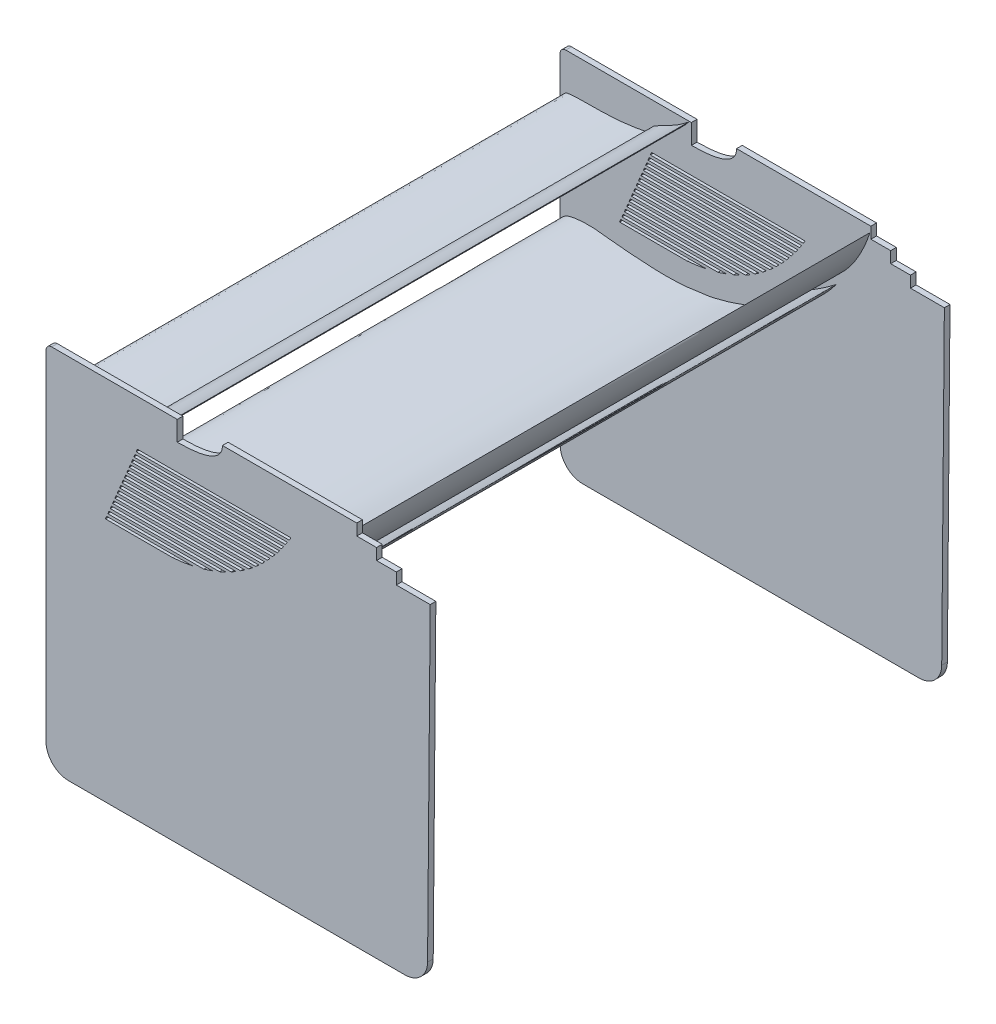
SolidWorks part; units mm, degrees
ref_plane "Front Plane" through (0, 0, 0) normal (0, 0, 1) x (1, 0, 0)
ref_plane "Top Plane" through (0, 0, 0) normal (0, 1, 0) x (1, 0, 0)
ref_plane "Right Plane" through (0, 0, 0) normal (1, 0, 0) x (0, 0, -1)
sketch "Sketch1" plane through (0, 0, 0) normal (0, 0, 1) x (1, 0, 0)
  line L0 (46.9575, 64.3181) -> (1074.8558, 208.7798) construction
sketch "Sketch2" plane through (0, 0, 0) normal (0, 0, 1) x (1, 0, 0)
  line L0 (0, 0) -> (400, 0) construction
  line L1 (0, 0) -> (399.6225, 66.8739) construction
  line L2 (0, 66.8739) -> (0, -66.8739) construction
  line L3 (10.0115, 66.8739) -> (10.0115, -116.1581) construction
  line L4 (20.0229, 66.8739) -> (20.0229, -116.1581) construction
  line L5 (30.0344, 66.8739) -> (30.0344, -116.1581) construction
  line L6 (40.0459, 66.8739) -> (40.0459, -116.1581) construction
  line L7 (50.0573, 66.8739) -> (50.0573, -116.1581) construction
  line L8 (60.0688, 66.8739) -> (60.0688, -116.1581) construction
  line L9 (70.0803, 66.8739) -> (70.0803, -116.1581) construction
  line L10 (80.0918, 66.8739) -> (80.0918, -116.1581) construction
  line L11 (90.1032, 66.8739) -> (90.1032, -116.1581) construction
  line L12 (100.1147, 66.8739) -> (100.1147, -116.1581) construction
  line L13 (110.1262, 66.8739) -> (110.1262, -116.1581) construction
  line L14 (120.1376, 66.8739) -> (120.1376, -116.1581) construction
  line L15 (130.1491, 66.8739) -> (130.1491, -116.1581) construction
  line L16 (140.1606, 66.8739) -> (140.1606, -116.1581) construction
  line L17 (150.172, 66.8739) -> (150.172, -116.1581) construction
  line L18 (160.1835, 66.8739) -> (160.1835, -116.1581) construction
  line L19 (170.195, 66.8739) -> (170.195, -116.1581) construction
  line L20 (180.2064, 66.8739) -> (180.2064, -116.1581) construction
  line L21 (190.2179, 66.8739) -> (190.2179, -116.1581) construction
  line L22 (200.2294, 66.8739) -> (200.2294, -116.1581) construction
  line L23 (210.2408, 66.8739) -> (210.2408, -116.1581) construction
  line L24 (220.2523, 66.8739) -> (220.2523, -116.1581) construction
  line L25 (230.2638, 66.8739) -> (230.2638, -116.1581) construction
  line L26 (240.2753, 66.8739) -> (240.2753, -116.1581) construction
  line L27 (250.2867, 66.8739) -> (250.2867, -116.1581) construction
  line L28 (260.2982, 66.8739) -> (260.2982, -116.1581) construction
  line L29 (270.3097, 66.8739) -> (270.3097, -116.1581) construction
  line L30 (280.3211, 66.8739) -> (280.3211, -116.1581) construction
  line L31 (290.3326, 66.8739) -> (290.3326, -116.1581) construction
  line L32 (300.3441, 66.8739) -> (300.3441, -116.1581) construction
  line L33 (310.3555, 66.8739) -> (310.3555, -116.1581) construction
  line L34 (320.367, 66.8739) -> (320.367, -116.1581) construction
  line L35 (330.3785, 66.8739) -> (330.3785, -116.1581) construction
  line L36 (340.3899, 66.8739) -> (340.3899, -116.1581) construction
  line L37 (350.4014, 66.8739) -> (350.4014, -116.1581) construction
  line L38 (360.4129, 66.8739) -> (360.4129, -116.1581) construction
  line L39 (370.4243, 66.8739) -> (370.4243, -116.1581) construction
  line L40 (380.4358, 66.8739) -> (380.4358, -116.1581) construction
  line L41 (390.4473, 66.8739) -> (390.4473, -116.1581) construction
  line L42 (400.4588, 66.8739) -> (400.4588, -116.1581) construction
  line L43 (836.1007, 66.8739) -> (-36.8556, 66.8739) construction
  line L44 (389.6225, 76.8739) -> (409.6225, 76.8739) construction
  line L45 (399.6225, 90.7703) -> (399.6225, 62.9774) construction
  line L46 (548.1427, 255.362) -> (478.7399, 156.2446) construction
  line L47 (488.7399, 146.2766) -> (482.6971, 142.1346) construction
  line L48 (389.6225, 76.8739) -> (488.7399, 146.2766) construction
  line L51 (488.7399, 194.8045) -> (488.7399, 123.7678) construction
  line L52 (478.7399, 201.6203) -> (478.7399, 116.9521) construction
  line L53 (478.7399, 156.2446) -> (614.5057, 156.2446) construction
  line L54 (389.6225, 83.3039) -> (389.6225, -27.4023) construction
  line L55 (478.7399, 146.2446) -> (614.5057, 146.2446) construction
  spline S0 degree 3 poles (8.4176, 12.2629) (-5.1, -0.6947) (8.0175, -15.4806) (19.5512, -21.724) (30.0167, -25.3022) (39.86, -28.8642) (50.0404, -30.6629) (60.0706, -32.2577) (70.0139, -34.2177) (80.101, -34.56) (90.0931, -35.3652) (100.112, -35.9529) (110.1282, -35.5072) (120.1532, -35.21) (130.1503, -34.2298) (140.19, -33.4102) (150.1782, -31.9134) (160.1704, -30.3713) (170.2408, -29.1636) (180.2083, -27.151) (190.2638, -25.3061) (200.2392, -22.8725) (210.2446, -20.4291) (220.2329, -17.8951) (230.3811, -15.7054) (240.3519, -12.3911) (253.5512, -7.3696) (266.9476, -2.8065) (280.4369, 1.6366) (290.3614, 5.8195) (300.4407, 10.0322) (310.3048, 14.8841) (323.8214, 20.8842) (337.3023, 27.2498) (350.2747, 34.8502) (364.0374, 41.2007) (378.0734, 50.4319) (389.2687, 56.9917) (404.9331, 70.6704) (388.8931, 60.8973) (380.9617, 56.8333) (370.3166, 52.1732) (360.4136, 47.7491) (350.4697, 43.0754) (340.4967, 38.8332) (330.4052, 35.261) (320.3498, 31.8494) (310.3583, 28.3259) (300.4869, 24.6622) (290.3218, 22.3006) (280.2904, 19.7619) (270.4267, 16.765) (260.336, 15.0613) (250.2769, 13.9588) (240.2662, 12.5783) (230.2787, 11.0679) (220.2867, 9.6964) (210.2433, 9.2404) (200.2287, 9.0345) (190.217, 8.2792) (180.2125, 9.1624) (170.1842, 8.7285) (160.1865, 9.5822) (150.1678, 9.9892) (140.1635, 10.7007) (130.146, 11.2145) (120.1214, 11.8409) (110.1328, 12.9697) (100.1148, 13.8501) (90.0938, 14.7159) (80.0796, 15.8427) (56.9177, 18.8475) (32.3828, 18.9634) (8.4176, 12.2629) (-5.1, -0.6947) (8.0175, -15.4806) knots -0.089629 -0.030705 -0.018228 0 0.022024 0.035622 0.048197 0.060585 0.072602 0.084545 0.096479 0.108284 0.12009 0.131879 0.143661 0.155449 0.167269 0.1791 0.190991 0.202897 0.214788 0.226766 0.238768 0.250864 0.262992 0.27512 0.287235 0.299601 0.31215 0.337082 0.349542 0.362249 0.375072 0.388091 0.40103 0.427261 0.440709 0.453892 0.481344 0.495528 0.510184 0.522428 0.535733 0.548643 0.561554 0.574511 0.587287 0.599816 0.612271 0.624763 0.637218 0.649381 0.661544 0.67375 0.685718 0.697586 0.709472 0.721375 0.733243 0.74504 0.756824 0.768611 0.780398 0.792175 0.803972 0.815766 0.827567 0.839363 0.851169 0.863006 0.874833 0.88666 0.89851 0.910371 0.969295 0.981772 1 1.022024 1.035622 1.048197 only from (0, 0) to (0, 0)
  spline S1 degree 3 poles (488.4807, 145.9571) (488.8121, 146.3498) (488.4243, 146.015) (488.0622, 145.7851) (487.2625, 145.1263) (486.2197, 144.3713) (484.8735, 143.3367) (483.2507, 142.1161) (481.3449, 140.7026) (479.1839, 139.1083) (476.7613, 137.3643) (474.1237, 135.4494) (471.2368, 133.4393) (468.1657, 131.2913) (464.8962, 129.0676) (461.4575, 126.7695) (457.874, 124.4106) (454.1513, 122.027) (450.3296, 119.6083) (446.4184, 117.1921) (442.4423, 114.7926) (438.4319, 112.4153) (434.4211, 110.0589) (430.4193, 107.7484) (426.4691, 105.4752) (422.5724, 103.27) (418.7829, 101.1054) (415.1038, 99.0189) (411.5811, 96.98) (408.2231, 95.0247) (405.0701, 93.1172) (402.1178, 91.3128) (399.4157, 89.5543) (396.9653, 87.8935) (394.7924, 86.3186) (392.9158, 84.83) (391.3498, 83.4309) (390.0835, 82.1509) (389.1526, 80.9646) (388.5665, 79.872) (388.3105, 78.8689) (388.4525, 77.9475) (389.0134, 77.2045) (389.9156, 76.685) (391.1282, 76.3842) (392.6501, 76.2546) (394.4851, 76.3138) (396.6232, 76.5794) (399.0459, 77.0357) (401.7358, 77.7205) (404.6757, 78.5968) (407.8392, 79.7049) (411.2008, 81.0269) (414.7209, 82.591) (418.3956, 84.3418) (422.1799, 86.3091) (426.0457, 88.48) (429.9704, 90.8288) (433.915, 93.3645) (437.8712, 96.0402) (441.7934, 98.8661) (445.6685, 101.7972) (449.4657, 104.8272) (453.1679, 107.924) (456.7615, 111.054) (460.2029, 114.2195) (463.5191, 117.343) (466.6501, 120.455) (469.6136, 123.4898) (472.3702, 126.4509) (474.954, 129.2656) (477.2978, 131.9605) (479.4562, 134.4635) (481.3811, 136.7846) (483.0779, 138.8974) (484.5577, 140.7696) (485.8099, 142.3825) (486.8479, 143.7389) (487.6258, 144.7686) (488.2511, 145.5957) (488.4807, 145.9571) (488.8121, 146.3498) (488.4243, 146.015) knots -0.00692 -0.003098 -0.00077 0 0.000781 0.003074 0.006931 0.012248 0.01903 0.027226 0.036785 0.04761 0.059602 0.072764 0.086897 0.102004 0.117939 0.134556 0.151858 0.169651 0.187838 0.206374 0.225065 0.243814 0.262569 0.281137 0.299514 0.317506 0.335105 0.352118 0.368488 0.384167 0.398955 0.412906 0.425872 0.437811 0.448585 0.458213 0.466669 0.473884 0.479894 0.484779 0.488743 0.492167 0.495628 0.499576 0.504487 0.510576 0.517943 0.526574 0.536524 0.54764 0.560015 0.573491 0.588031 0.603544 0.619912 0.637089 0.654944 0.673346 0.692212 0.711461 0.73091 0.750475 0.770022 0.789461 0.808651 0.827458 0.84582 0.863559 0.880666 0.896945 0.912322 0.926718 0.939993 0.952161 0.96306 0.972662 0.980906 0.987733 0.99308 0.996902 0.99923 1 1.000781 1.003074 1.006931 only from (488.7399, 146.2766) to (488.7399, 146.2766)
  spline S2 degree 3 poles (548.0012, 254.9703) (548.1874, 255.456) (547.9279, 255.0069) (547.6584, 254.6667) (547.113, 253.7707) (546.3674, 252.702) (545.4246, 251.265) (544.2794, 249.5582) (542.9279, 247.5728) (541.3924, 245.3297) (539.6567, 242.8564) (537.7725, 240.1482) (535.6814, 237.266) (533.4602, 234.1907) (531.0746, 230.977) (528.5519, 227.6359) (525.9111, 224.1885) (523.1453, 220.6711) (520.2967, 217.0873) (517.3615, 213.4761) (514.3589, 209.8593) (511.316, 206.2523) (508.2658, 202.665) (505.209, 199.1247) (502.189, 195.6372) (499.1976, 192.2326) (496.2952, 188.9024) (493.4722, 185.6835) (490.783, 182.5623) (488.2235, 179.5757) (485.844, 176.7031) (483.6219, 173.9957) (481.6239, 171.4156) (479.834, 169.0126) (478.2807, 166.784) (476.9821, 164.7365) (475.9505, 162.878) (475.1658, 161.233) (474.6707, 159.7892) (474.4739, 158.5497) (474.5629, 157.5056) (475.0053, 156.672) (475.7887, 156.1483) (476.824, 155.9518) (478.0833, 156.0678) (479.5813, 156.4503) (481.3159, 157.1174) (483.2715, 158.0828) (485.4358, 159.3251) (487.7794, 160.8747) (490.2983, 162.6906) (492.9538, 164.8026) (495.7276, 167.1848) (498.5723, 169.8513) (501.5026, 172.7478) (504.4658, 175.8877) (507.4391, 179.2493) (510.4095, 182.8005) (513.3367, 186.5371) (516.2285, 190.4114) (519.0377, 194.4179) (521.767, 198.5093) (524.3889, 202.6695) (526.8977, 206.8618) (529.2916, 211.0497) (531.5283, 215.2209) (533.6592, 219.3103) (535.617, 223.3271) (537.4402, 227.2144) (539.0902, 230.9623) (540.6237, 234.5128) (541.9677, 237.8689) (543.1982, 240.9799) (544.2661, 243.8393) (545.1852, 246.4237) (545.977, 248.7058) (546.6373, 250.6644) (547.1783, 252.3065) (547.5794, 253.5497) (547.9019, 254.5484) (548.0012, 254.9703) (548.1874, 255.456) (547.9279, 255.0069) knots -0.00692 -0.003098 -0.00077 0 0.000781 0.003074 0.006931 0.012248 0.01903 0.027226 0.036785 0.04761 0.059602 0.072764 0.086897 0.102004 0.117939 0.134556 0.151858 0.169651 0.187838 0.206374 0.225065 0.243814 0.262569 0.281137 0.299514 0.317506 0.335105 0.352118 0.368488 0.384167 0.398955 0.412906 0.425872 0.437811 0.448585 0.458213 0.466669 0.473884 0.479894 0.484779 0.488743 0.492167 0.495628 0.499576 0.504487 0.510576 0.517943 0.526574 0.536524 0.54764 0.560015 0.573491 0.588031 0.603544 0.619912 0.637089 0.654944 0.673346 0.692212 0.711461 0.73091 0.750475 0.770022 0.789461 0.808651 0.827458 0.84582 0.863559 0.880666 0.896945 0.912322 0.926718 0.939993 0.952161 0.96306 0.972662 0.980906 0.987733 0.99308 0.996902 0.99923 1 1.000781 1.003074 1.006931 only from (548.1427, 255.362) to (548.1427, 255.362)
  point P7 (0, 0)
  point P94 (399.6225, 76.8739)
  point P100 (399.6225, 76.8739)
  point P108 (399.6225, 66.8739)
  point P112 (389.6225, 76.8739)
  point P126 (488.7399, 146.2766)
  point P130 (488.7399, 156.2766)
  point P136 (488.7399, 159.2862)
  point P142 (478.7399, 159.2862)
  dimension "D1" = 9.5
  dimension "D3" = 405.1793
  dimension "D4" = 400
  dimension "D5" = 121
  dimension "D6" = 10
  dimension "D7" = 35
  dimension "D8" = 10
  dimension "D9" = 55
  dimension "D10" = 10
  dimension "D11" = 121
  dimension "D12" = 10
  dimension "D13" = 79.3707
  dimension "D2" = 41
extrude "Boss-Extrude1" add sketch "Sketch2" along normal blind 900
ref_plane "Plane1" through (0, 0, 900) normal (0, 0, 1) x (1, 0, 0)
sketch "Sketch5" plane through (0, 0, 0) normal (0, 0, 1) x (1, 0, 0)
  line L0 (550, 266.2835) -> (550, -383.7165) construction
  line L1 (10, 266.2835) -> (550, 266.2835)
  line L2 (0, 256.2835) -> (0, 0)
  line L5 (550, 266.2835) -> (550, 246.2835)
  line L6 (550, 246.2835) -> (585, 246.2835)
  line L7 (585, 246.2835) -> (585, 226.2835)
  line L8 (585, 226.2835) -> (620, 226.2835)
  line L9 (620, 226.2835) -> (620, 206.2835)
  line L10 (620, 206.2835) -> (680, 206.2835)
  line L11 (675, -383.7165) -> (425, -383.7165) construction
  line L14 (0, 0) -> (0, -343.7165)
  line L15 (40, -383.7165) -> (635.3375, -383.7165)
  line L16 (675.3361, -344.0554) -> (680, 206.2835)
  arc A0 (675.3361, -344.0554) -> (635.3375, -383.7165) centre (635.3375, -343.7165) cw
  arc A1 (40, -383.7165) -> (0, -343.7165) centre (40, -343.7165) cw
  arc A2 (10, 266.2835) -> (0, 256.2835) centre (10, 256.2835) ccw
  point P6 (550, -383.7165)
  point P16 (-20.6859, 188.16)
  point P20 (0, -383.7165)
  point P23 (0, 266.2835)
  dimension "D10" = 40
  dimension "D11" = 10
  dimension "D1" = 266.2835
  dimension "D2" = 675
  dimension "D3" = 35
  dimension "D4" = 20
  dimension "D5" = 20
  dimension "D6" = 35
  dimension "D7" = 20
  dimension "D8" = 60
  dimension "D9" = 650
ref_plane "Plane2" through (0, 0, 450) normal (0, 0, 1) x (1, 0, 0)
extrude "Boss-Extrude2" add sketch "Sketch5" against normal blind 10 contours L1 L5 L6 L7 L8 L9 L10 L16 A0 L15 A1 L14 L2 A2
sketch "Sketch6" plane through (0, 0, 0) normal (0, 0, 1) x (1, 0, 0)
  line L0 (0, 197.4544) -> (160, 197.4544) construction
  line L1 (0, 256.2835) -> (0, 0) construction
  line L2 (160, 197.4544) -> (258.2982, 266.2835) construction
  line L3 (10, 266.2835) -> (550, 266.2835) construction
  line L4 (164.6138, 214.9761) -> (164.7238, 214.6645)
  line L5 (164.6138, 214.9761) -> (8.3018, 197.4544) construction
  line L6 (8.3018, 197.4544) -> (160, 197.4544) construction
  line L7 (164.7238, 214.6645) -> (215.8682, 214.6645) construction
  line L8 (164.6138, 224.6645) -> (215.8682, 224.6645) construction
  line L9 (227.0142, 264.2269) -> (227.1245, 264.1177)
  line L10 (227.0142, 264.2269) -> (164.4495, 224.8752) construction
  spline S0 degree 3 poles (164.7238, 214.6645) (164.6485, 214.6279) (164.3478, 214.4816) (163.6724, 214.1552) (162.55, 213.6175) (160.9852, 212.8783) (158.985, 211.9502) (156.5581, 210.8501) (153.7156, 209.5966) (150.4706, 208.2115) (146.8388, 206.7177) (142.8379, 205.1402) (138.4882, 203.505) (133.8122, 201.8376) (128.8347, 200.165) (123.5829, 198.5127) (118.0862, 196.9059) (112.3762, 195.3683) (106.4862, 193.9228) (100.4517, 192.5894) (94.3097, 191.3873) (88.0988, 190.332) (81.8589, 189.4374) (75.6309, 188.7132) (69.4566, 188.1671) (63.3778, 187.8027) (57.4367, 187.6199) (51.6745, 187.6158) (46.1317, 187.7835) (40.8475, 188.1122) (35.859, 188.5889) (31.201, 189.198) (26.9054, 189.9203) (23.0013, 190.7368) (19.5141, 191.6263) (16.4656, 192.568) (13.8731, 193.5412) (11.7498, 194.5273) (10.1003, 195.5106) (8.9257, 196.4838) (8.2062, 197.4661) (8.027, 198.5089) (8.4702, 199.4674) (9.4095, 200.2316) (10.7736, 200.88) (12.5817, 201.4358) (14.8279, 201.9066) (17.5019, 202.295) (20.5864, 202.6069) (24.0614, 202.8473) (27.9044, 203.0253) (32.0912, 203.1493) (36.5959, 203.231) (41.3918, 203.282) (46.4505, 203.3154) (51.7431, 203.3445) (57.2393, 203.3835) (62.9083, 203.4456) (68.7179, 203.5435) (74.6355, 203.6891) (80.6273, 203.8921) (86.6588, 204.1602) (92.6952, 204.4989) (98.701, 204.9104) (104.6405, 205.3951) (110.4779, 205.9495) (116.1778, 206.5676) (121.7051, 207.2412) (127.0255, 207.9592) (132.1056, 208.7094) (136.9131, 209.4769) (141.4173, 210.2472) (145.589, 211.0042) (149.4009, 211.7324) (152.8279, 212.4165) (155.8468, 213.0419) (158.4374, 213.5952) (160.5819, 214.065) (162.2656, 214.441) (163.4767, 214.7155) (164.2068, 214.8826) (164.5322, 214.9574) (164.6138, 214.9761) knots 0 0 0 0 0.00078 0.003113 0.006984 0.012366 0.019224 0.027511 0.037173 0.048145 0.060358 0.073731 0.088182 0.103618 0.119946 0.137065 0.15487 0.173257 0.192113 0.211327 0.230786 0.250373 0.269972 0.289465 0.308737 0.32767 0.346151 0.364066 0.381307 0.397768 0.413347 0.427952 0.441493 0.45389 0.465074 0.474985 0.48358 0.490835 0.496756 0.501407 0.504969 0.507873 0.510777 0.514327 0.518939 0.524778 0.531895 0.540287 0.549922 0.560751 0.572712 0.585736 0.599745 0.614657 0.630386 0.646842 0.66393 0.681556 0.699621 0.718024 0.736663 0.755434 0.774231 0.792948 0.811476 0.829709 0.847536 0.864851 0.881546 0.897515 0.912656 0.926869 0.940056 0.952128 0.962998 0.972589 0.98083 0.98766 0.993027 0.996891 0.999221 1 1 1 1
  spline S1 degree 3 poles (227.1245, 264.1177) (227.1002, 264.0868) (227.003, 263.9634) (226.7842, 263.6871) (226.4198, 263.23) (225.9096, 262.5971) (225.2539, 261.7952) (224.4531, 260.8332) (223.508, 259.7213) (222.4196, 258.4713) (221.1899, 257.0962) (219.8214, 255.6101) (218.3172, 254.0282) (216.6816, 252.3659) (214.9197, 250.6397) (213.0376, 248.8659) (211.0426, 247.0612) (208.9433, 245.2421) (206.749, 243.4251) (204.4708, 241.6258) (202.1201, 239.8601) (199.7103, 238.1424) (197.2553, 236.4866) (194.7705, 234.9053) (192.2719, 233.4103) (189.7765, 232.0117) (187.302, 230.7181) (184.8667, 229.5366) (182.489, 228.4727) (180.1876, 227.5298) (177.9809, 226.71) (175.8869, 226.0139) (173.9229, 225.4398) (172.1051, 224.9857) (170.4487, 224.6478) (168.967, 224.4218) (167.6717, 224.3024) (166.5721, 224.2846) (165.6734, 224.3626) (164.9776, 224.5336) (164.4722, 224.8016) (164.183, 225.2058) (164.1741, 225.7018) (164.4148, 226.2172) (164.8587, 226.7706) (165.5094, 227.3758) (166.3627, 228.0347) (167.4137, 228.7464) (168.6539, 229.5097) (170.0739, 230.3229) (171.6622, 231.1849) (173.4069, 232.0945) (175.2947, 233.0513) (177.3119, 234.0548) (179.4438, 235.1046) (181.6755, 236.2005) (183.9912, 237.3423) (186.3753, 238.5292) (188.8115, 239.76) (191.2835, 241.0331) (193.7752, 242.3457) (196.2704, 243.6939) (198.7531, 245.073) (201.208, 246.4765) (203.6199, 247.8975) (205.9744, 249.327) (208.2576, 250.7553) (210.4566, 252.1717) (212.559, 253.5646) (214.5532, 254.9218) (216.4286, 256.2306) (218.1752, 257.4784) (219.784, 258.6526) (221.2465, 259.7409) (222.5553, 260.7317) (223.7036, 261.6142) (224.6856, 262.3786) (225.4961, 263.0162) (226.131, 263.5199) (226.5868, 263.8839) (226.8612, 264.104) (226.9835, 264.2023) (227.0142, 264.2269) knots 0 0 0 0 0.00078 0.003113 0.006984 0.012366 0.019224 0.027511 0.037173 0.048145 0.060358 0.073731 0.088182 0.103618 0.119946 0.137065 0.15487 0.173257 0.192113 0.211327 0.230786 0.250373 0.269972 0.289465 0.308737 0.32767 0.346151 0.364066 0.381307 0.397768 0.413347 0.427952 0.441493 0.45389 0.465074 0.474985 0.48358 0.490835 0.496756 0.501407 0.504969 0.507873 0.510777 0.514327 0.518939 0.524778 0.531895 0.540287 0.549922 0.560751 0.572712 0.585736 0.599745 0.614657 0.630386 0.646842 0.66393 0.681556 0.699621 0.718024 0.736663 0.755434 0.774231 0.792948 0.811476 0.829709 0.847536 0.864851 0.881546 0.897515 0.912656 0.926869 0.940056 0.952128 0.962998 0.972589 0.98083 0.98766 0.993027 0.996891 0.999221 1 1 1 1
  dimension "D1" = 145
  dimension "D2" = 160
  dimension "D3" = 120
  dimension "D4" = 10
extrude "Boss-Extrude3" add sketch "Sketch6" along normal blind 900
sketch "Sketch7" plane through (0, 0, 0) normal (0, 0, 1) x (1, 0, 0)
  line L0 (232.2613, 266.2835) -> (232.2613, 231.2835)
  line L1 (10, 266.2835) -> (550, 266.2835) construction
  line L2 (232.2613, 266.2835) -> (312.2613, 266.2835)
  line L3 (312.2613, 266.2835) -> (312.2613, 231.2835) construction
  line L4 (312.2613, 231.2835) -> (232.2613, 231.2835) construction
  spline S1 degree 2 poles (312.2613, 266.2835) (312.2613, 231.2835) (232.2613, 231.2835) knots 0 0 0 1 1 1
  point P6 (339.6097, 232.0046)
  dimension "D1" = 35
  dimension "D2" = 80
extrude "Cut-Extrude1" cut sketch "Sketch7" against normal blind 900
sketch "Sketch8" plane through (0, 0, 0) normal (0, 0, 1) x (1, 0, 0)
  line L4 (161.8037, 185.2784) -> (433.5275, 185.2784)
  line L5 (159.7086, 180.2784) -> (430.4208, 180.2784)
  line L16 (164.9224, 130.2784) -> (452.6678, 130.2784) [skipped]
  line L26 (67.2058, 135.2784) -> (220.4617, 135.2784) [skipped]
  line L27 (76.1878, 140.2784) -> (244.1181, 140.2784) [skipped]
  line L28 (85.1699, 145.2784) -> (267.7746, 145.2784) [skipped]
  line L29 (94.1519, 150.2784) -> (291.431, 150.2784) [skipped]
  line L30 (103.1339, 155.2784) -> (315.0875, 155.2784) [skipped]
  line L31 (112.116, 160.2784) -> (338.7439, 160.2784) [skipped]
  line L32 (121.098, 165.2784) -> (362.4003, 165.2784) [skipped]
  line L33 (139.0621, 175.2784) -> (409.7132, 175.2784) [skipped]
  line L34 (130.08, 170.2784) -> (386.0568, 170.2784) [skipped]
  line L36 (155.5185, 170.2784) -> (423.8746, 170.2784)
  line L37 (157.6135, 175.2784) -> (427.2053, 175.2784)
  line L40 (151.3284, 160.2784) -> (416.8376, 160.2784)
  line L41 (153.4234, 165.2784) -> (420.4214, 165.2784)
  line L44 (147.1382, 150.2784) -> (409.2419, 150.2784)
  line L45 (149.2333, 155.2784) -> (413.1145, 155.2784)
  line L48 (142.9481, 140.2784) -> (401.0022, 140.2784)
  line L49 (145.0432, 145.2784) -> (405.2087, 145.2784)
  line L52 (138.758, 130.2784) -> (392.0089, 130.2784)
  line L53 (140.853, 135.2784) -> (396.6078, 135.2784)
  line L56 (134.5679, 120.2784) -> (382.1176, 120.2784)
  line L57 (136.6629, 125.2784) -> (387.1863, 125.2784)
  line L60 (130.3777, 110.2784) -> (371.1304, 110.2784)
  line L61 (132.4728, 115.2784) -> (376.7761, 115.2784)
  line L64 (126.1876, 100.2784) -> (358.7645, 100.2784)
  line L65 (128.2827, 105.2784) -> (365.1422, 105.2784)
  line L68 (121.9975, 90.2784) -> (344.5889, 90.2784)
  line L69 (124.0926, 95.2784) -> (351.9385, 95.2784)
  line L72 (117.8074, 80.2784) -> (327.8864, 80.2784)
  line L73 (119.9024, 85.2784) -> (336.6165, 85.2784)
  line L76 (113.6173, 70.2784) -> (307.2861, 70.2784)
  line L77 (115.7123, 75.2784) -> (318.2064, 75.2784)
  line L80 (109.4271, 60.2784) -> (279.3938, 60.2784)
  line L81 (111.5222, 65.2784) -> (294.6475, 65.2784)
  line L84 (105.237, 50.2784) -> (224.5387, 50.2784)
  line L85 (107.3321, 55.2784) -> (259.3865, 55.2784)
  line L88 (161.8037, 185.2784) -> (159.7086, 180.2784)
  line L89 (119.9024, 85.2784) -> (117.8074, 80.2784)
  line L114 (107.3321, 55.2784) -> (105.237, 50.2784)
  line L115 (111.5222, 65.2784) -> (109.4271, 60.2784)
  line L116 (115.7123, 75.2784) -> (113.6173, 70.2784)
  line L117 (124.0926, 95.2784) -> (121.9975, 90.2784)
  line L118 (128.2827, 105.2784) -> (126.1876, 100.2784)
  line L119 (132.4728, 115.2784) -> (130.3777, 110.2784)
  line L120 (157.6135, 175.2784) -> (155.5185, 170.2784)
  line L121 (153.4234, 165.2784) -> (151.3284, 160.2784)
  line L122 (149.2333, 155.2784) -> (147.1382, 150.2784)
  line L123 (145.0432, 145.2784) -> (142.9481, 140.2784)
  line L124 (140.853, 135.2784) -> (138.758, 130.2784)
  line L125 (136.6629, 125.2784) -> (134.5679, 120.2784)
  spline S0 degree 2 poles (433.5275, 185.2784) (431.986, 182.755) (430.4208, 180.2784) knots 0 0 0 0.017044 0.017044 0.017044
  spline S1 degree 3 poles (420.4214, 165.2784) (419.2361, 163.5933) (418.0415, 161.9267) (416.8376, 160.2784) knots 0.070227 0.070227 0.070227 0.070227 0.088712 0.088712 0.088712 0.088712
  spline S2 degree 3 poles (427.2053, 175.2784) (426.1036, 173.5948) (424.9934, 171.9282) (423.8746, 170.2784) knots 0.034417 0.034417 0.034417 0.034417 0.052137 0.052137 0.052137 0.052137
  spline S3 degree 3 poles (413.1145, 155.2784) (411.8338, 153.5916) (410.543, 151.9249) (409.2419, 150.2784) knots 0.107617 0.107617 0.107617 0.107617 0.126974 0.126974 0.126974 0.126974
  spline S4 degree 3 poles (405.2087, 145.2784) (403.8178, 143.5894) (402.4157, 141.9228) (401.0022, 140.2784) knots 0.146816 0.146816 0.146816 0.146816 0.167181 0.167181 0.167181 0.167181
  spline S5 degree 3 poles (396.6078, 135.2784) (395.0875, 133.5868) (393.5545, 131.9201) (392.0089, 130.2784) knots 0.188113 0.188113 0.188113 0.188113 0.209663 0.209663 0.209663 0.209663
  spline S6 degree 3 poles (387.1863, 125.2784) (385.5111, 123.5834) (383.8215, 121.9167) (382.1176, 120.2784) knots 0.231889 0.231889 0.231889 0.231889 0.254857 0.254857 0.254857 0.254857
  spline S7 degree 3 poles (376.7761, 115.2784) (374.9109, 113.5789) (373.029, 111.9122) (371.1304, 110.2784) knots 0.27865 0.27865 0.27865 0.27865 0.303361 0.303361 0.303361 0.303361
  spline S8 degree 3 poles (365.1422, 105.2784) (363.0361, 103.5728) (360.9102, 101.9061) (358.7645, 100.2784) knots 0.329106 0.329106 0.329106 0.329106 0.356027 0.356027 0.356027 0.356027
  spline S9 degree 3 poles (351.9385, 95.2784) (349.5129, 93.5638) (347.0631, 91.8972) (344.5889, 90.2784) knots 0.384302 0.384302 0.384302 0.384302 0.414159 0.414159 0.414159 0.414159
  spline S10 degree 3 poles (336.6165, 85.2784) (333.738, 83.5495) (330.828, 81.8829) (327.8864, 80.2784) knots 0.445896 0.445896 0.445896 0.445896 0.47992 0.47992 0.47992 0.47992
  spline S11 degree 3 poles (318.2064, 75.2784) (314.6113, 73.523) (310.9712, 71.8563) (307.2861, 70.2784) knots 0.516814 0.516814 0.516814 0.516814 0.557452 0.557452 0.557452 0.557452
  spline S12 degree 3 poles (294.6475, 65.2784) (289.6416, 63.4567) (284.557, 61.79) (279.3938, 60.2784) knots 0.60328 0.60328 0.60328 0.60328 0.657004 0.657004 0.657004 0.657004
  spline S13 degree 3 poles (259.3865, 55.2784) (248.1179, 52.9273) (236.502, 51.2606) (224.5387, 50.2784) knots 0.725082 0.725082 0.725082 0.725082 0.837974 0.837974 0.837974 0.837974
  dimension "D1" = 14
  dimension "D6" = 12
extrude "Cut-Extrude2" cut sketch "Sketch8" against normal blind 900
mirror "Mirror1" about plane through (0, 0, 450) normal (0, 0, 1) of "Cut-Extrude2", "Cut-Extrude1", "Boss-Extrude2"
